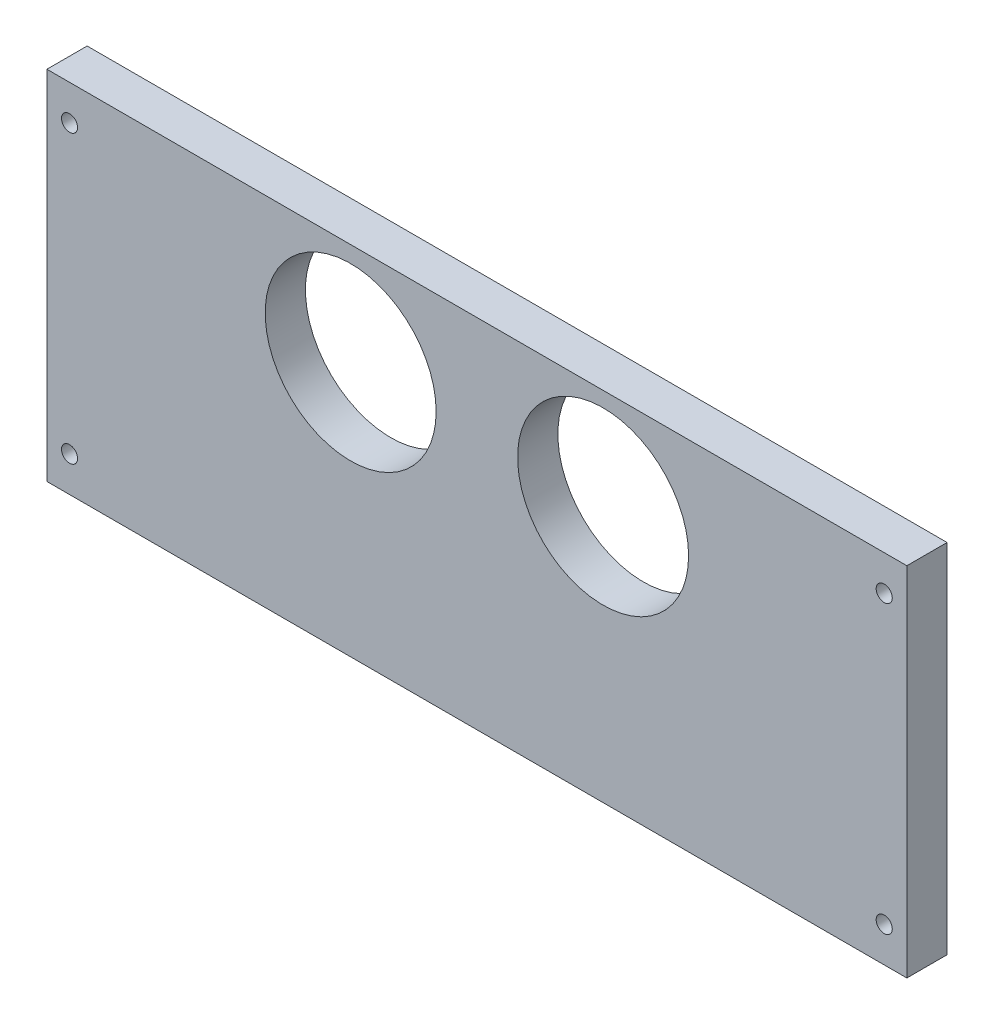
SolidWorks part; units mm, degrees
ref_plane "Front Plane" through (0, 0, 0) normal (0, 0, 1) x (1, 0, 0)
ref_plane "Top Plane" through (0, 0, 0) normal (0, 1, 0) x (1, 0, 0)
ref_plane "Right Plane" through (0, 0, 0) normal (1, 0, 0) x (0, 0, -1)
sketch "Sketch1" plane through (0, 0, 0) normal (0, 0, 1) x (1, 0, 0)
  line L1 (-42.75, 17.75) -> (42.75, 17.75)
  line L2 (-42.75, 17.75) -> (-42.75, -17.75)
  line L3 (-42.75, -17.75) -> (42.75, -17.75)
  line L4 (42.75, 17.75) -> (42.75, -17.75)
  line L5 (-42.75, 17.75) -> (42.75, -17.75) construction
  line L6 (-42.75, -17.75) -> (42.75, 17.75) construction
  point P0 (0, 0)
  dimension "D1" = 85.5
  dimension "D2" = 35.5
extrude "Boss-Extrude1" add sketch "Sketch1" against normal blind 4
sketch "Sketch2" plane through (0, 0, 0) normal (0, 0, 1) x (1, 0, 0)
  line L0 (42.75, -17.75) -> (42.75, 17.75) construction
  line L1 (42.75, 17.75) -> (-42.75, 17.75) construction
  line L2 (0, 0) -> (0, 6.2167) construction
  line L3 (0, 0) -> (5.0447, 0) construction
  circle A0 centre (40.5, 14.25) radius 1
  circle A1 centre (-40.5, 14.25) radius 1
  circle A2 centre (40.5, -14.25) radius 1
  circle A3 centre (-40.5, -14.25) radius 1
  point P0 (40.5, 14.25)
  point P9 (-40.5, 14.25)
  point P12 (40.5, -14.25)
  point P14 (-40.5, -14.25)
  dimension "D1" = 2.25
  dimension "D3" = 2
  dimension "D2" = 3.5
hole_wizard "M2 Tapped Hole1" positions "Sketch2" profile "Sketch3" tap size "M2" standard "ISO"
sketch "Sketch3" plane through (40.5, 14.25, 0) normal (1, 0, 0) x (0, -1, 0)
  line L0 (0, 0) -> (0, 6.4807)
  line L1 (0, 6.4807) -> (0.8, 6)
  line L2 (0.8, 6) -> (0.8, 0)
  line L5 (0.8, 0) -> (0, 0)
  line L10 (0, 6.4807) -> (-0.8, 6) construction
  line L11 (0, -6.35) -> (0, 107.95) construction
  dimension "Tap Drill Dia." = 1.6
  dimension "Tap Drill Depth" = 6
  dimension "Drill Angle" = 118
cosmetic thread "Hole Thread1" parameters "D1"=4, "D2"=2
cosmetic thread "Hole Thread2" parameters "D1"=4, "D2"=2
cosmetic thread "Hole Thread3" parameters "D1"=4, "D2"=2
cosmetic thread "Hole Thread4" parameters "D1"=4, "D2"=2
sketch "Sketch4" plane through (0, 0, 0) normal (0, 0, 1) x (1, 0, 0)
  line L0 (42.75, 17.75) -> (-42.75, 17.75) construction
  line L1 (0, 0) -> (0, 20.0818) construction
  circle A0 centre (12.55, 7.75) radius 8.5
  circle A1 centre (-12.55, 7.6172) radius 8.5
  dimension "D1" = 17
  dimension "D5" = 17
  dimension "D2" = 10
  dimension "D3" = 25.1
  dimension "D4" = 12.55
extrude "Cut-Extrude1" cut sketch "Sketch4" against normal blind 10
